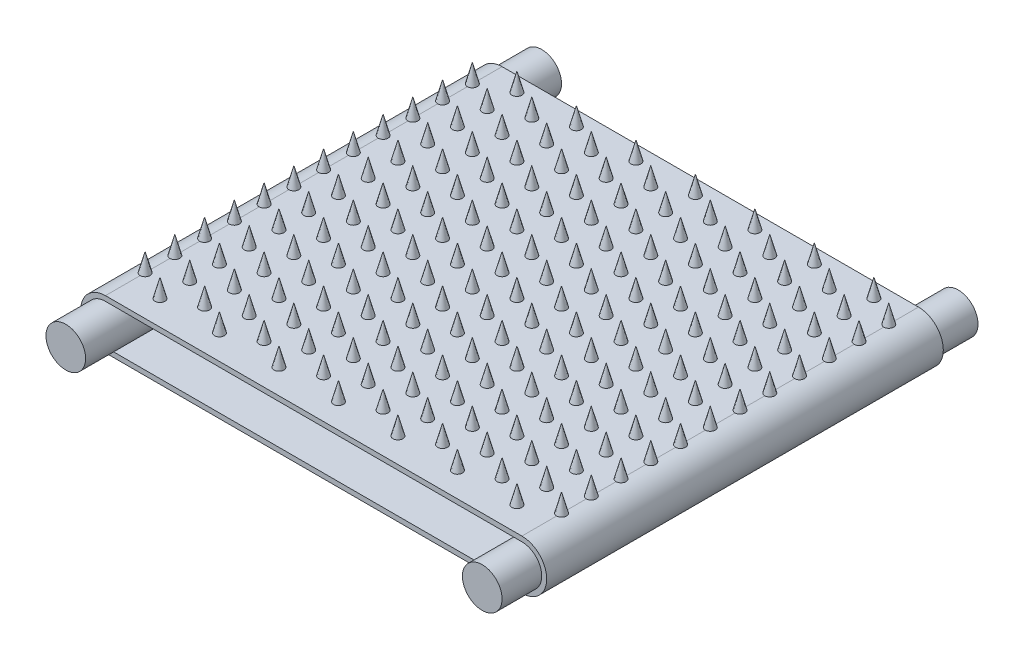
SolidWorks part; units mm, degrees
ref_plane "Front Plane" through (0, 0, 0) normal (0, 0, 1) x (1, 0, 0)
ref_plane "Top Plane" through (0, 0, 0) normal (0, 1, 0) x (1, 0, 0)
ref_plane "Right Plane" through (0, 0, 0) normal (1, 0, 0) x (0, 0, -1)
sketch "Sketch1" plane through (0, 0, 0) normal (0, 0, 1) x (1, 0, 0)
  line L0 (0, 0) -> (1066.8, 0)
  line L1 (0, 63.5) -> (1066.8, 63.5)
  line L2 (0, -63.5) -> (1066.8, -63.5)
  line L3 (0, 50.8) -> (1066.8, 50.8)
  line L4 (0, -50.8) -> (1066.8, -50.8)
  circle A0 centre (0, 0) radius 50.8
  circle A1 centre (1066.8, 0) radius 50.8
  circle A2 centre (1066.8, 0) radius 63.5
  circle A3 centre (0, 0) radius 63.5
extrude "Boss-Extrude1" add sketch "Sketch1" along normal blind 1016 contours L3 A3 L4 A0 | A3 L3 A2 L1 | A3 L2 A2 L4 | A2 L3 A1 L4
sketch "Sketch2" plane through (0, 0, 1016) normal (0, 0, 1) x (1, 0, 0)
  circle A0 centre (0, 0) radius 50.8
  circle A1 centre (1066.8, 0) radius 50.8
extrude "Boss-Extrude2" add sketch "Sketch2" against normal blind 1117.6
sketch "Sketch3" plane through (0, 0, 1016) normal (0, 0, 1) x (1, 0, 0)
  circle A0 centre (0, 0) radius 50.8
  circle A1 centre (1066.8, 0) radius 50.8
extrude "Boss-Extrude3" add sketch "Sketch3" along normal blind 101.6
sketch "Sketch4" plane through (0, 63.5, 0) normal (0, 1, 0) x (1, 0, 0)
  line L0 (0, 0) -> (0, -76.2)
  line L1 (0, -1016) -> (0, 0) construction
  line L2 (0, 0) -> (76.2, 0)
  line L3 (76.2, 0) -> (76.2, -38.1)
  circle A0 centre (0, -76.2) radius 12.7
  circle A13 centre (0, -152.4) radius 12.7
  circle A14 centre (0, -228.6) radius 12.7
  circle A15 centre (0, -304.8) radius 12.7
  circle A16 centre (0, -381) radius 12.7
  circle A17 centre (0, -457.2) radius 12.7
  circle A18 centre (0, -533.4) radius 12.7
  circle A19 centre (0, -609.6) radius 12.7
  circle A20 centre (0, -685.8) radius 12.7
  circle A21 centre (0, -762) radius 12.7
  circle A22 centre (0, -838.2) radius 12.7
  circle A23 centre (0, -914.4) radius 12.7
  circle A24 centre (2.54, -914.4) radius 12.7 [skipped]
  circle A25 centre (2.54, -838.2) radius 12.7 [skipped]
  circle A26 centre (2.54, -762) radius 12.7 [skipped]
  circle A27 centre (2.54, -685.8) radius 12.7 [skipped]
  circle A28 centre (2.54, -609.6) radius 12.7 [skipped]
  circle A29 centre (2.54, -533.4) radius 12.7 [skipped]
  circle A30 centre (2.54, -457.2) radius 12.7 [skipped]
  circle A31 centre (2.54, -381) radius 12.7 [skipped]
  circle A32 centre (2.54, -304.8) radius 12.7 [skipped]
  circle A33 centre (2.54, -228.6) radius 12.7 [skipped]
  circle A34 centre (2.54, -152.4) radius 12.7 [skipped]
  circle A35 centre (2.54, -76.2) radius 12.7 [skipped]
  circle A36 centre (76.2, -38.1) radius 12.7
  circle A50 centre (76.2, -114.3) radius 12.7
  circle A51 centre (76.2, -190.5) radius 12.7
  circle A52 centre (76.2, -266.7) radius 12.7
  circle A53 centre (76.2, -342.9) radius 12.7
  circle A54 centre (76.2, -419.1) radius 12.7
  circle A55 centre (76.2, -495.3) radius 12.7
  circle A56 centre (76.2, -571.5) radius 12.7
  circle A57 centre (76.2, -647.7) radius 12.7
  circle A58 centre (76.2, -723.9) radius 12.7
  circle A59 centre (76.2, -800.1) radius 12.7
  circle A60 centre (76.2, -876.3) radius 12.7
  circle A61 centre (76.2, -952.5) radius 12.7
  circle A62 centre (78.74, -38.1) radius 12.7 [skipped]
  circle A63 centre (78.74, -114.3) radius 12.7 [skipped]
  circle A64 centre (78.74, -190.5) radius 12.7 [skipped]
  circle A65 centre (78.74, -266.7) radius 12.7 [skipped]
  circle A66 centre (78.74, -342.9) radius 12.7 [skipped]
  circle A67 centre (78.74, -419.1) radius 12.7 [skipped]
  circle A68 centre (78.74, -495.3) radius 12.7 [skipped]
  circle A69 centre (78.74, -571.5) radius 12.7 [skipped]
  circle A70 centre (78.74, -647.7) radius 12.7 [skipped]
  circle A71 centre (78.74, -723.9) radius 12.7 [skipped]
  circle A72 centre (78.74, -800.1) radius 12.7 [skipped]
  circle A73 centre (78.74, -876.3) radius 12.7 [skipped]
  circle A74 centre (78.74, -952.5) radius 12.7 [skipped]
  circle A75 centre (152.4, -76.2) radius 12.7
  circle A76 centre (152.4, -152.4) radius 12.7
  circle A77 centre (152.4, -228.6) radius 12.7
  circle A78 centre (152.4, -304.8) radius 12.7
  circle A79 centre (152.4, -381) radius 12.7
  circle A80 centre (152.4, -457.2) radius 12.7
  circle A81 centre (152.4, -533.4) radius 12.7
  circle A82 centre (152.4, -609.6) radius 12.7
  circle A83 centre (152.4, -685.8) radius 12.7
  circle A84 centre (152.4, -762) radius 12.7
  circle A85 centre (152.4, -838.2) radius 12.7
  circle A86 centre (152.4, -914.4) radius 12.7
  circle A87 centre (304.8, -76.2) radius 12.7
  circle A88 centre (304.8, -152.4) radius 12.7
  circle A89 centre (304.8, -228.6) radius 12.7
  circle A90 centre (304.8, -304.8) radius 12.7
  circle A91 centre (304.8, -381) radius 12.7
  circle A92 centre (304.8, -457.2) radius 12.7
  circle A93 centre (304.8, -533.4) radius 12.7
  circle A94 centre (304.8, -609.6) radius 12.7
  circle A95 centre (304.8, -685.8) radius 12.7
  circle A96 centre (304.8, -762) radius 12.7
  circle A97 centre (304.8, -838.2) radius 12.7
  circle A98 centre (304.8, -914.4) radius 12.7
  circle A99 centre (457.2, -76.2) radius 12.7
  circle A100 centre (457.2, -152.4) radius 12.7
  circle A101 centre (457.2, -228.6) radius 12.7
  circle A102 centre (457.2, -304.8) radius 12.7
  circle A103 centre (457.2, -381) radius 12.7
  circle A104 centre (457.2, -457.2) radius 12.7
  circle A105 centre (457.2, -533.4) radius 12.7
  circle A106 centre (457.2, -609.6) radius 12.7
  circle A107 centre (457.2, -685.8) radius 12.7
  circle A108 centre (457.2, -762) radius 12.7
  circle A109 centre (457.2, -838.2) radius 12.7
  circle A110 centre (457.2, -914.4) radius 12.7
  circle A111 centre (609.6, -76.2) radius 12.7
  circle A112 centre (609.6, -152.4) radius 12.7
  circle A113 centre (609.6, -228.6) radius 12.7
  circle A114 centre (609.6, -304.8) radius 12.7
  circle A115 centre (609.6, -381) radius 12.7
  circle A116 centre (609.6, -457.2) radius 12.7
  circle A117 centre (609.6, -533.4) radius 12.7
  circle A118 centre (609.6, -609.6) radius 12.7
  circle A119 centre (609.6, -685.8) radius 12.7
  circle A120 centre (609.6, -762) radius 12.7
  circle A121 centre (609.6, -838.2) radius 12.7
  circle A122 centre (609.6, -914.4) radius 12.7
  circle A123 centre (762, -76.2) radius 12.7
  circle A124 centre (762, -152.4) radius 12.7
  circle A125 centre (762, -228.6) radius 12.7
  circle A126 centre (762, -304.8) radius 12.7
  circle A127 centre (762, -381) radius 12.7
  circle A128 centre (762, -457.2) radius 12.7
  circle A129 centre (762, -533.4) radius 12.7
  circle A130 centre (762, -609.6) radius 12.7
  circle A131 centre (762, -685.8) radius 12.7
  circle A132 centre (762, -762) radius 12.7
  circle A133 centre (762, -838.2) radius 12.7
  circle A134 centre (762, -914.4) radius 12.7
  circle A135 centre (914.4, -76.2) radius 12.7
  circle A136 centre (914.4, -152.4) radius 12.7
  circle A137 centre (914.4, -228.6) radius 12.7
  circle A138 centre (914.4, -304.8) radius 12.7
  circle A139 centre (914.4, -381) radius 12.7
  circle A140 centre (914.4, -457.2) radius 12.7
  circle A141 centre (914.4, -533.4) radius 12.7
  circle A142 centre (914.4, -609.6) radius 12.7
  circle A143 centre (914.4, -685.8) radius 12.7
  circle A144 centre (914.4, -762) radius 12.7
  circle A145 centre (914.4, -838.2) radius 12.7
  circle A146 centre (914.4, -914.4) radius 12.7
  circle A147 centre (1066.8, -76.2) radius 12.7
  circle A148 centre (1066.8, -152.4) radius 12.7
  circle A149 centre (1066.8, -228.6) radius 12.7
  circle A150 centre (1066.8, -304.8) radius 12.7
  circle A151 centre (1066.8, -381) radius 12.7
  circle A152 centre (1066.8, -457.2) radius 12.7
  circle A153 centre (1066.8, -533.4) radius 12.7
  circle A154 centre (1066.8, -609.6) radius 12.7
  circle A155 centre (1066.8, -685.8) radius 12.7
  circle A156 centre (1066.8, -762) radius 12.7
  circle A157 centre (1066.8, -838.2) radius 12.7
  circle A158 centre (1066.8, -914.4) radius 12.7
  circle A159 centre (228.6, -38.1) radius 12.7
  circle A160 centre (228.6, -114.3) radius 12.7
  circle A161 centre (228.6, -190.5) radius 12.7
  circle A162 centre (228.6, -266.7) radius 12.7
  circle A163 centre (228.6, -342.9) radius 12.7
  circle A164 centre (228.6, -419.1) radius 12.7
  circle A165 centre (228.6, -495.3) radius 12.7
  circle A166 centre (228.6, -571.5) radius 12.7
  circle A167 centre (228.6, -647.7) radius 12.7
  circle A168 centre (228.6, -723.9) radius 12.7
  circle A169 centre (228.6, -800.1) radius 12.7
  circle A170 centre (228.6, -876.3) radius 12.7
  circle A171 centre (228.6, -952.5) radius 12.7
  circle A172 centre (381, -38.1) radius 12.7
  circle A173 centre (381, -114.3) radius 12.7
  circle A174 centre (381, -190.5) radius 12.7
  circle A175 centre (381, -266.7) radius 12.7
  circle A176 centre (381, -342.9) radius 12.7
  circle A177 centre (381, -419.1) radius 12.7
  circle A178 centre (381, -495.3) radius 12.7
  circle A179 centre (381, -571.5) radius 12.7
  circle A180 centre (381, -647.7) radius 12.7
  circle A181 centre (381, -723.9) radius 12.7
  circle A182 centre (381, -800.1) radius 12.7
  circle A183 centre (381, -876.3) radius 12.7
  circle A184 centre (381, -952.5) radius 12.7
  circle A185 centre (533.4, -38.1) radius 12.7
  circle A186 centre (533.4, -114.3) radius 12.7
  circle A187 centre (533.4, -190.5) radius 12.7
  circle A188 centre (533.4, -266.7) radius 12.7
  circle A189 centre (533.4, -342.9) radius 12.7
  circle A190 centre (533.4, -419.1) radius 12.7
  circle A191 centre (533.4, -495.3) radius 12.7
  circle A192 centre (533.4, -571.5) radius 12.7
  circle A193 centre (533.4, -647.7) radius 12.7
  circle A194 centre (533.4, -723.9) radius 12.7
  circle A195 centre (533.4, -800.1) radius 12.7
  circle A196 centre (533.4, -876.3) radius 12.7
  circle A197 centre (533.4, -952.5) radius 12.7
  circle A198 centre (685.8, -38.1) radius 12.7
  circle A199 centre (685.8, -114.3) radius 12.7
  circle A200 centre (685.8, -190.5) radius 12.7
  circle A201 centre (685.8, -266.7) radius 12.7
  circle A202 centre (685.8, -342.9) radius 12.7
  circle A203 centre (685.8, -419.1) radius 12.7
  circle A204 centre (685.8, -495.3) radius 12.7
  circle A205 centre (685.8, -571.5) radius 12.7
  circle A206 centre (685.8, -647.7) radius 12.7
  circle A207 centre (685.8, -723.9) radius 12.7
  circle A208 centre (685.8, -800.1) radius 12.7
  circle A209 centre (685.8, -876.3) radius 12.7
  circle A210 centre (685.8, -952.5) radius 12.7
  circle A211 centre (838.2, -38.1) radius 12.7
  circle A212 centre (838.2, -114.3) radius 12.7
  circle A213 centre (838.2, -190.5) radius 12.7
  circle A214 centre (838.2, -266.7) radius 12.7
  circle A215 centre (838.2, -342.9) radius 12.7
  circle A216 centre (838.2, -419.1) radius 12.7
  circle A217 centre (838.2, -495.3) radius 12.7
  circle A218 centre (838.2, -571.5) radius 12.7
  circle A219 centre (838.2, -647.7) radius 12.7
  circle A220 centre (838.2, -723.9) radius 12.7
  circle A221 centre (838.2, -800.1) radius 12.7
  circle A222 centre (838.2, -876.3) radius 12.7
  circle A223 centre (838.2, -952.5) radius 12.7
  circle A224 centre (990.6, -38.1) radius 12.7
  circle A225 centre (990.6, -114.3) radius 12.7
  circle A226 centre (990.6, -190.5) radius 12.7
  circle A227 centre (990.6, -266.7) radius 12.7
  circle A228 centre (990.6, -342.9) radius 12.7
  circle A229 centre (990.6, -419.1) radius 12.7
  circle A230 centre (990.6, -495.3) radius 12.7
  circle A231 centre (990.6, -571.5) radius 12.7
  circle A232 centre (990.6, -647.7) radius 12.7
  circle A233 centre (990.6, -723.9) radius 12.7
  circle A234 centre (990.6, -800.1) radius 12.7
  circle A235 centre (990.6, -876.3) radius 12.7
  circle A236 centre (990.6, -952.5) radius 12.7
  point P9 (0, 0)
  point P10 (0, 0)
  point P431 (0, 0)
  point P432 (0, 0)
  point P433 (0, 0)
  point P434 (0, 0)
  point P435 (0, 0)
  dimension "D1" = 2
  dimension "D3" = 2
  dimension "D2" = 12
  dimension "D4" = 13
  dimension "D5" = 8
  dimension "D6" = 7
extrude "Boss-Extrude4" add sketch "Sketch4" along normal blind 50.8 draft 15 contours A56 | A165 | A166 | A0 | A36 | A13 | A14 | A15 | A16 | A17 | A18 | A19 | A20 | A21 | A22 | A23 | A61 | A60 | A59 | A58 | A57 | A55 | A54 | A53 | A52 | A50 | A51 | A75 | A76 | A77 | A78 | A79 | A80 | A81 | A82 | A83 | A84 | A85 | A86 | A159 | A160 | A161 | A162 | A163 | A164 | A167 | A168 | A169 | A170 | A171 | A98 | A97 | A96 | A95 | A94 | A93 | A92 | A91 | A90 | A89 | A88 | A87 | A172 | A173 | A174 | A175 | A176 | A177 | A178 | A179 | A180 | A181 | A182 | A183 | A184 | A110 | A109 | A108 | A107 | A106 | A105 | A104 | A103 | A102 | A101 | A100 | A99 | A185 | A186 | A187 | A188 | A189 | A190 | A191 | A192 | A193 | A194 | A195 | A196 | A197 | A111 | A112 | A113 | A114 | A115 | A116 | A117 | A118 | A119 | A120 | A121 | A122 | A210 | A209 | A207 | A208 | A206 | A205 | A204 | A203 | A202 | A201 | A200 | A199 | A198 | A123 | A124 | A125 | A126 | A127 | A128 | A129 | A130 | A131 | A132 | A133 | A134 | A223 | A222 | A221 | A220 | A219 | A218 | A217 | A216 | A215 | A214 | A213 | A212 | A211 | A135 | A224 | A147 | A225 | A136 | A226 | A148 | A149 | A227 | A137 | A138 | A228 | A150 | A151 | A229 | A139 | A140 | A141 | A230 | A152 | A153 | A154 | A232 | A142 | A231 | A155 | A233 | A143 | A144 | A145 | A146 | A234 | A235 | A236 | A158 | A157 | A156
